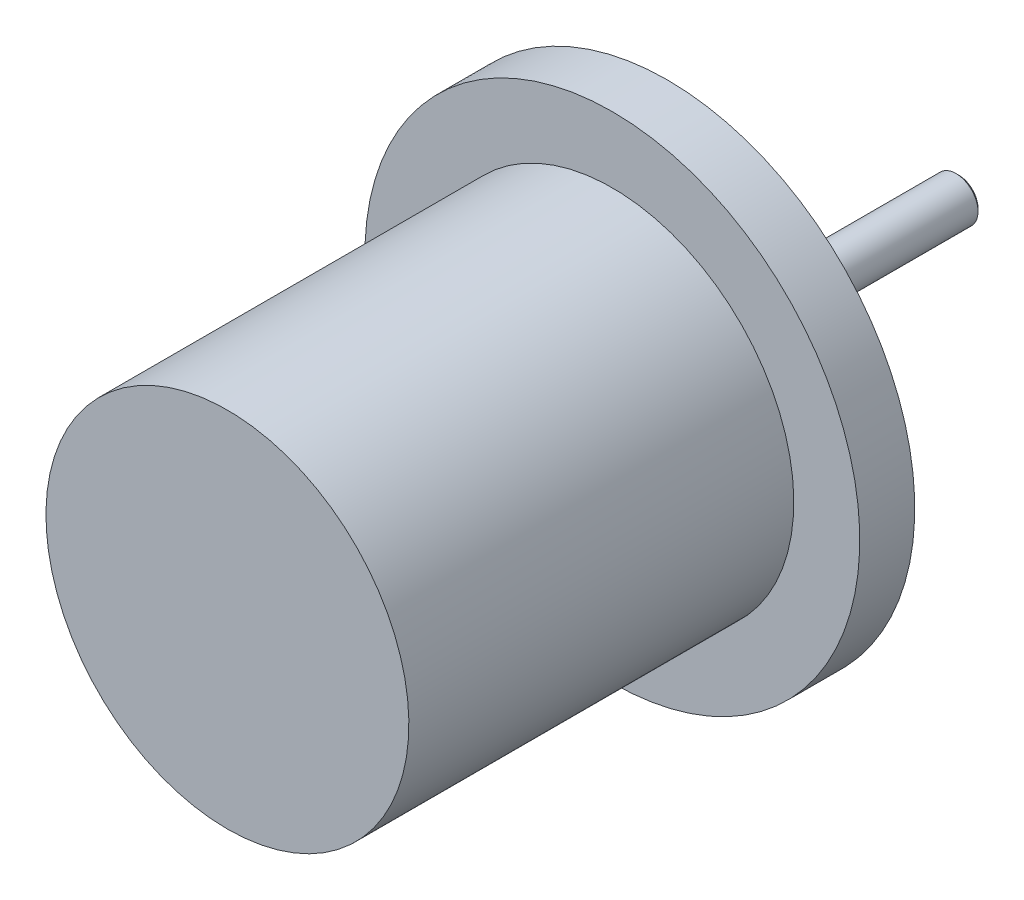
SolidWorks part; units mm, degrees
material "Cast Stainless Steel"
ref_plane "Front" through (0, 0, 0) normal (0, 0, 1) x (1, 0, 0)
ref_plane "Top" through (0, 0, 0) normal (0, 1, 0) x (1, 0, 0)
ref_plane "Right" through (0, 0, 0) normal (1, 0, 0) x (0, 0, -1)
sketch "Sketch1" plane through (0, 0, 0) normal (1, 0, 0) x (0, 0, -1)
  line L0 (-67.7839, 0) -> (65.2161, 0)
  line L1 (12.2161, 45) -> (12.2161, 17.5)
  line L2 (12.2161, 45) -> (2.2161, 45)
  line L3 (2.2161, 45) -> (2.2161, 33)
  line L4 (2.2161, 33) -> (-67.7839, 33)
  line L5 (-67.7839, 33) -> (-67.7839, 0)
  line L6 (15.2161, 6) -> (15.2161, 17.5)
  line L7 (15.2161, 17.5) -> (12.2161, 17.5)
  line L8 (31.2161, 6) -> (31.2161, 4)
  line L9 (31.2161, 6) -> (15.2161, 6)
  line L10 (31.2161, 4) -> (65.2161, 4)
  line L11 (65.2161, 4) -> (65.2161, 0)
  dimension "D1" = 16
  dimension "D2" = 10
  dimension "D3" = 6
  dimension "D4" = 70
  dimension "D5" = 3
  dimension "D6" = 33
  dimension "D7" = 4
  dimension "D8" = 34
  dimension "D9" = 45
revolve "Revolve1" add sketch "Sketch1" angle 360 about L0
ref_plane "Plane1" through (0, 6, 0) normal (0, 1, 0) x (1, 0, 0)
sketch "Sketch2" plane through (0, 6, 0) normal (0, 1, 0) x (1, 0, 0)
  line L2 (-2.025, 20.7323) -> (-2.025, 27.6823)
  line L4 (2.025, 27.6823) -> (2.025, 20.7323)
  arc A0 (2.025, 27.6823) -> (-2.025, 27.6823) centre (0, 27.6823) ccw
  arc A1 (-2.025, 20.7323) -> (2.025, 20.7323) centre (0, 20.7323) ccw
  dimension "D1" = 4.05
  dimension "D2" = 4.05
extrude "Cut-Extrude1" cut sketch "Sketch2" against normal blind 2.5
chamfer "Chamfer1" distance 0.5 angle 45 1 edges at (0, -6, -31.2161)
sketch "Sketch7" plane through (0, 0, -12.2161) normal (0, 0, -1) x (-1, 0, 0)
  line L0 (0, 0) -> (0, 47.9811) construction
  line L1 (0, 0) -> (33.9277, 33.9277) construction
  line L2 (0, 0) -> (47.9811, 0) construction
  line L3 (0, 0) -> (33.9277, -33.9277) construction
  line L4 (0, 0) -> (0, -47.9811) construction
  line L5 (0, 0) -> (-33.9277, -33.9277) construction
  line L6 (0, 0) -> (-47.9811, 0) construction
  line L7 (0, 0) -> (-33.9277, 33.9277) construction
  circle A0 centre (0, 0) radius 35
  circle A1 centre (0, 35) radius 3
  circle A2 centre (24.7487, 24.7487) radius 3
  circle A3 centre (35, 0) radius 3
  circle A4 centre (24.7487, -24.7487) radius 3
  circle A5 centre (0, -35) radius 3
  circle A6 centre (-24.7487, -24.7487) radius 3
  circle A7 centre (-35, 0) radius 3
  circle A8 centre (-24.7487, 24.7487) radius 3
  point P13 (0, 0)
  point P31 (0, 0)
  dimension "D1" = 70
  dimension "D3" = 6
  dimension "D2" = 8
  dimension "D4" = 8
extrude "Cut-Extrude4" cut sketch "Sketch7" against normal blind 3 contours A0 A8 | A0 A8 | A0 A7 | A0 A7 | A0 A6 | A0 A6 | A0 A5 | A0 A5 | A0 A4 | A0 A4 | A0 A3 | A0 A3 | A0 A2 | A0 A2 | A0 A1 | A0 A1
cosmetic thread "Cosmetic Thread1" parameters "D2"=10
cosmetic thread "Cosmetic Thread2" parameters "D2"=10
cosmetic thread "Cosmetic Thread3" parameters "D2"=10
cosmetic thread "Cosmetic Thread4" parameters "D2"=10
cosmetic thread "Cosmetic Thread5" parameters "D2"=10
cosmetic thread "Cosmetic Thread6" parameters "D2"=10
cosmetic thread "Cosmetic Thread7" parameters "D2"=10
cosmetic thread "Cosmetic Thread8" parameters "D2"=10
sketch "Sketch8" plane through (0, 0, -65.2161) normal (0, 0, -1) x (-1, 0, 0)
  circle A0 centre (0, 0) radius 1.5
  dimension "D1" = 3
extrude "Cut-Extrude5" cut sketch "Sketch8" against normal blind 5
cosmetic thread "Cosmetic Thread11" parameters "D2"=6
chamfer "Chamfer2" distance 0.5 angle 45 1 edges at (0, -4, -65.2161)
sketch "Sketch9" plane through (0, 0, -12.2161) normal (0, 0, -1) x (-1, 0, 0)
  point P0 (-24.7487, 24.7487)
  point P1 (0, 35)
  point P3 (24.7487, 24.7487)
  point P5 (35, 0)
  point P7 (24.7487, -24.7487)
  point P9 (0, -35)
  point P11 (-24.7487, -24.7487)
  point P13 (-35, 0)
sketch "Sketch10" plane through (0, 0, -12.2161) normal (0, 0, -1) x (-1, 0, 0)
  point P0 (-35, 0)
  point P1 (35, 0)
  point P3 (0, -35)
  point P5 (0, 35)
